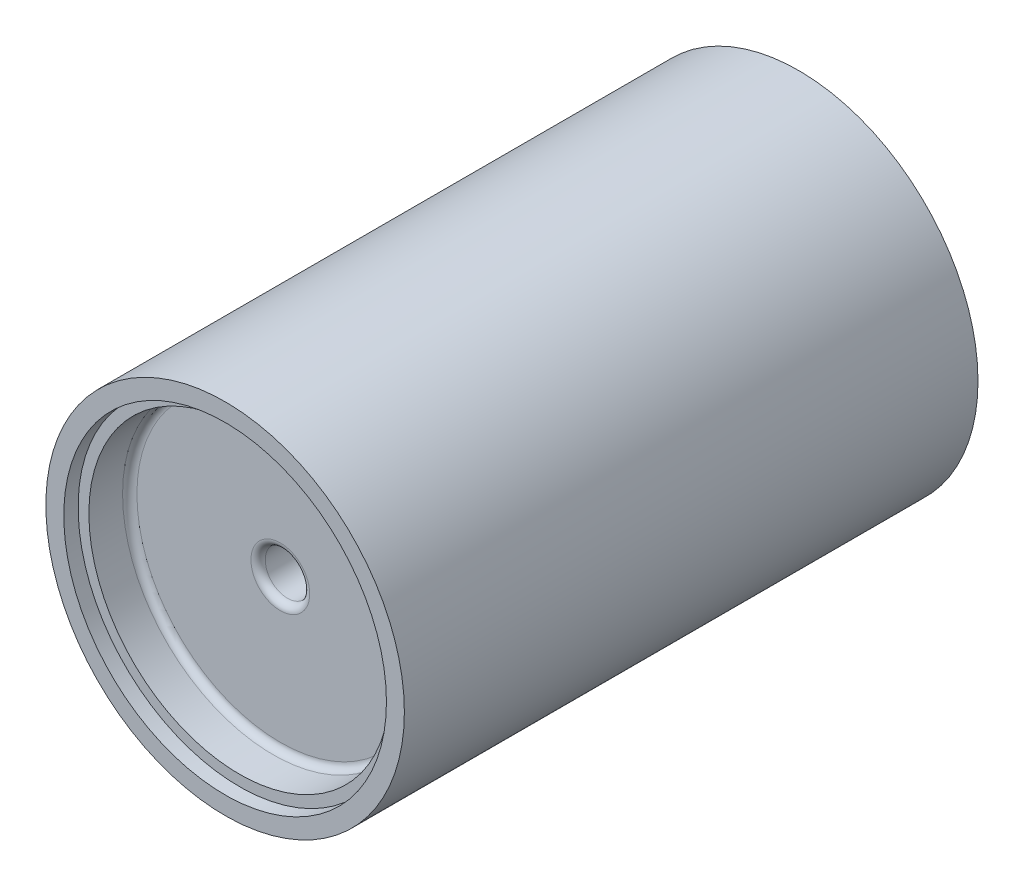
SolidWorks part; units mm, degrees
ref_plane "Plano frontal" through (0, 0, 0) normal (0, 0, 1) x (1, 0, 0)
ref_plane "Plano superior" through (0, 0, 0) normal (0, 1, 0) x (1, 0, 0)
ref_plane "Plano direito" through (0, 0, 0) normal (1, 0, 0) x (0, 0, -1)
sketch "Esboço1" plane through (0, 0, 0) normal (0, 0, 1) x (1, 0, 0)
  circle A0 centre (0, 0) radius 25
  circle A1 centre (0, 0) radius 3.1
  dimension "D1" = 50
  dimension "D2" = 6.2
extrude "Ressalto-extrusão1" add sketch "Esboço1" along normal mid plane 80
sketch "Esboço3" plane through (0, 0, 40) normal (0, 0, 1) x (1, 0, 0)
  circle A0 centre (0, 0) radius 21
  circle A1 centre (0, 0) radius 25 construction
  dimension "D1" = 4
extrude "Corte-extrusão1" cut sketch "Esboço3" against normal blind 7.7
sketch "Esboço4" plane through (0, 0, -40) normal (0, 0, -1) x (-1, 0, 0)
  circle A0 centre (0, 0) radius 21
  circle A1 centre (0, 0) radius 25 construction
  dimension "D1" = 4
extrude "Corte-extrusão2" cut sketch "Esboço4" against normal blind 7.7
fillet "Filete1" radius 1 4 edges at (-21, 0, -32.3) (21, 0, 32.3) (-3.1, 0, -32.3) (3.1, 0, 32.3)
ref_plane "Plano2" through (0, 0, 40) normal (0, 0, 1) x (1, 0, 0)
ref_plane "Plano3" through (0, 0, 37.5) normal (0, 0, 1) x (1, 0, 0)
ref_plane "Plano4" through (0, 0, 42) normal (0, 0, 1) x (1, 0, 0)
sketch "Esboço10" plane through (0, 0, 42) normal (0, 0, 1) x (1, 0, 0)
  circle A0 centre (0, 0) radius 25 construction
  circle A1 centre (0, 0) radius 25 construction
sketch "Esboço11" plane through (0, 0, 40) normal (0, 0, 1) x (1, 0, 0)
  circle A0 centre (0, 0) radius 22.5
  circle A1 centre (0, 0) radius 21 construction
  circle A2 centre (0, 0) radius 21
  dimension "D1" = 1.5
extrude "Corte-extrusão3" cut sketch "Esboço11" against normal blind 2
sketch "Esboço12" plane through (0, 0, -40) normal (0, 0, -1) x (-1, 0, 0)
  circle A0 centre (0, 0) radius 22.5
  circle A1 centre (0, 0) radius 21 construction
  circle A2 centre (0, 0) radius 21
  dimension "D1" = 1.5
extrude "Corte-extrusão4" cut sketch "Esboço12" against normal blind 2
